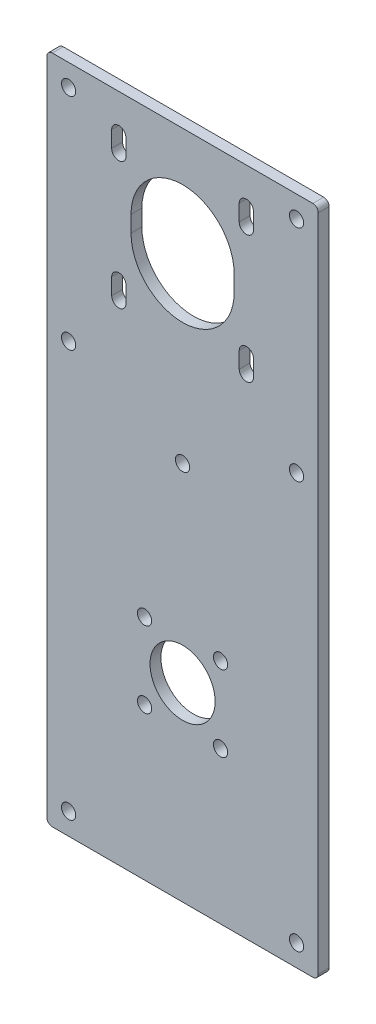
SolidWorks part; units mm, degrees
ref_plane "前视基准面" through (0, 0, 0) normal (0, 0, 1) x (1, 0, 0)
ref_plane "上视基准面" through (0, 0, 0) normal (0, 1, 0) x (1, 0, 0)
ref_plane "右视基准面" through (0, 0, 0) normal (1, 0, 0) x (0, 0, -1)
sketch "Model" plane through (0, 0, 0) normal (0, 0, 1) x (1, 0, 0)
  line L0 (0, 491.1858) -> (0, 0) construction
  line L1 (0, 0) -> (450.0461, 0) construction
  line L64 (225.2263, 294.0325) -> (148.7981, 294.0325) construction
  line L65 (191.0347, 265.8424) -> (191.0347, 327.1861) construction
  line L66 (179.4699, 270.5325) -> (152.8206, 270.5325) construction
  line L67 (217.1597, 314.5325) -> (217.1597, 320.5325)
  line L68 (211.9097, 320.5325) -> (211.9097, 314.5325)
  line L69 (217.1597, 267.5325) -> (217.1597, 273.5325)
  line L70 (211.9097, 273.5325) -> (211.9097, 267.5325)
  line L71 (172.0347, 297.0325) -> (172.0347, 291.0325)
  line L72 (210.0347, 291.0325) -> (210.0347, 297.0325)
  line L73 (239.0347, 334.0325) -> (143.0347, 334.0325)
  line L74 (241.0347, 89.0325) -> (241.0347, 332.0325)
  line L75 (143.0347, 87.0325) -> (239.0347, 87.0325)
  line L76 (141.0347, 332.0325) -> (141.0347, 89.0325)
  line L77 (170.1597, 267.5325) -> (170.1597, 273.5325)
  line L78 (164.9097, 273.5325) -> (164.9097, 267.5325)
  line L79 (170.1597, 314.5325) -> (170.1597, 320.5325)
  line L80 (164.9097, 320.5325) -> (164.9097, 314.5325)
  arc A0 (211.9097, 314.5325) -> (217.1597, 314.5325) centre (214.5347, 314.5325) ccw
  arc A1 (217.1597, 320.5325) -> (211.9097, 320.5325) centre (214.5347, 320.5325) ccw
  arc A2 (211.9097, 267.5325) -> (217.1597, 267.5325) centre (214.5347, 267.5325) ccw
  arc A3 (217.1597, 273.5325) -> (211.9097, 273.5325) centre (214.5347, 273.5325) ccw
  arc A4 (210.0347, 297.0325) -> (172.0347, 297.0325) centre (191.0347, 297.0325) ccw
  arc A5 (172.0347, 291.0325) -> (210.0347, 291.0325) centre (191.0347, 291.0325) ccw
  arc A6 (143.0347, 334.0325) -> (141.0347, 332.0325) centre (143.0347, 332.0325) ccw
  arc A7 (241.0347, 332.0325) -> (239.0347, 334.0325) centre (239.0347, 332.0325) ccw
  arc A8 (239.0347, 87.0325) -> (241.0347, 89.0325) centre (239.0347, 89.0325) ccw
  arc A9 (141.0347, 89.0325) -> (143.0347, 87.0325) centre (143.0347, 89.0325) ccw
  circle A10 centre (191.0347, 157.0325) radius 12
  arc A11 (164.9097, 267.5325) -> (170.1597, 267.5325) centre (167.5347, 267.5325) ccw
  arc A12 (170.1597, 273.5325) -> (164.9097, 273.5325) centre (167.5347, 273.5325) ccw
  arc A13 (164.9097, 314.5325) -> (170.1597, 314.5325) centre (167.5347, 314.5325) ccw
  arc A14 (170.1597, 320.5325) -> (164.9097, 320.5325) centre (167.5347, 320.5325) ccw
  circle A15 centre (177.0347, 171.0325) radius 2.625
  circle A16 centre (205.0347, 171.0325) radius 2.625
  circle A17 centre (177.0347, 143.0325) radius 2.625
  circle A18 centre (205.0347, 143.0325) radius 2.625
  circle A19 centre (149.0347, 95.0325) radius 2.625
  circle A20 centre (233.0347, 95.0325) radius 2.625
  circle A21 centre (149.0347, 245.0325) radius 2.625
  circle A22 centre (233.0347, 245.0325) radius 2.625
  circle A23 centre (149.0347, 326.0325) radius 2.625
  circle A24 centre (233.0347, 326.0325) radius 2.625
  circle A25 centre (191.0347, 227.0325) radius 2.625
extrude "凸台-拉伸1" add sketch "Model" along normal blind 4
